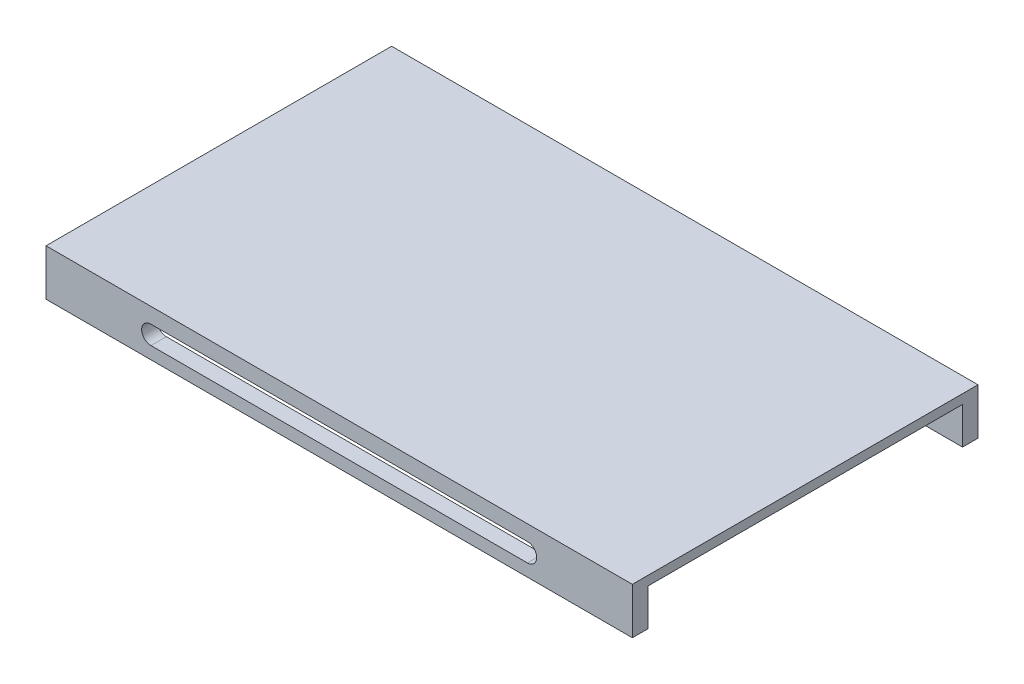
SolidWorks part; units mm, degrees
ref_plane "Front Plane" through (0, 0, 0) normal (0, 0, 1) x (1, 0, 0)
ref_plane "Top Plane" through (0, 0, 0) normal (0, 1, 0) x (1, 0, 0)
ref_plane "Right Plane" through (0, 0, 0) normal (1, 0, 0) x (0, 0, -1)
sketch "Sketch1" plane through (0, 0, 0) normal (0, 1, 0) x (1, 0, 0)
  line L0 (0, 0) -> (190, 0)
  line L1 (0, 0) -> (0, -112)
  line L2 (0, -112) -> (190, -112)
  line L3 (190, -112) -> (190, 0)
extrude "Boss-Extrude1" add sketch "Sketch1" along normal blind 15
sketch "Sketch2" plane through (0, 0, 112) normal (0, 0, 1) x (1, 0, 0)
  line L0 (95, 15) -> (95, 0) construction
  line L1 (0, 15) -> (190, 15) construction
  line L2 (0, 0) -> (190, 0) construction
  line L3 (-25.0751, 7) -> (227.2595, 7) construction
  line L4 (0, 15) -> (34, 15) construction
  line L5 (34, 15) -> (34, 0) construction
  line L6 (-23.6995, 10) -> (201.7116, 10) construction
  line L7 (34, 7) -> (28, 7) construction
  line L8 (0, 15) -> (0, 0) construction
  line L9 (34, 10) -> (156, 10)
  line L10 (34, 4) -> (156, 4)
  arc A0 (34, 10) -> (34, 4) centre (34, 7) ccw
  arc A1 (156, 10) -> (156, 4) centre (156, 7) cw
  point P20 (95, 4)
  point P25 (95, 10)
  dimension "D1" = 8
  dimension "D2" = 3
  dimension "D3" = 34
sketch "Sketch5" plane through (190, 0, 0) normal (1, 0, 0) x (0, 0, -1)
  line L0 (-5, 21.1587) -> (-5, -14.5215) construction
  line L1 (0, 15) -> (0, 0) construction
  line L2 (-115.7759, 12) -> (7.4829, 12) construction
  line L3 (-112, 15) -> (0, 15) construction
  line L4 (-107, 24.5182) -> (-107, -14.5215) construction
  line L5 (-112, 15) -> (-112, 0) construction
  line L6 (-107, 12) -> (-5, 12)
  line L7 (-5, 12) -> (-5, 0)
  line L8 (-5, 0) -> (-107, 0)
  line L9 (-112, 0) -> (0, 0) construction
  line L10 (-107, 0) -> (-107, 12)
  dimension "D1" = 5
  dimension "D2" = 3
  dimension "D3" = 5
extrude "Cut-Extrude3" cut sketch "Sketch5" against normal through all
extrude "Cut-Extrude4" cut sketch "Sketch2" against normal blind 10
sketch "Sketch6" plane through (0, 0, 0) normal (0, 0, -1) x (-1, 0, 0)
  line L0 (-190, 7.5) -> (0, 7.5) construction
  line L1 (-190, 15) -> (-190, 0) construction
  line L2 (0, 15) -> (0, 0) construction
  circle A0 centre (-95, 7.5) radius 3
extrude "Cut-Extrude5" cut sketch "Sketch6" against normal blind 10
